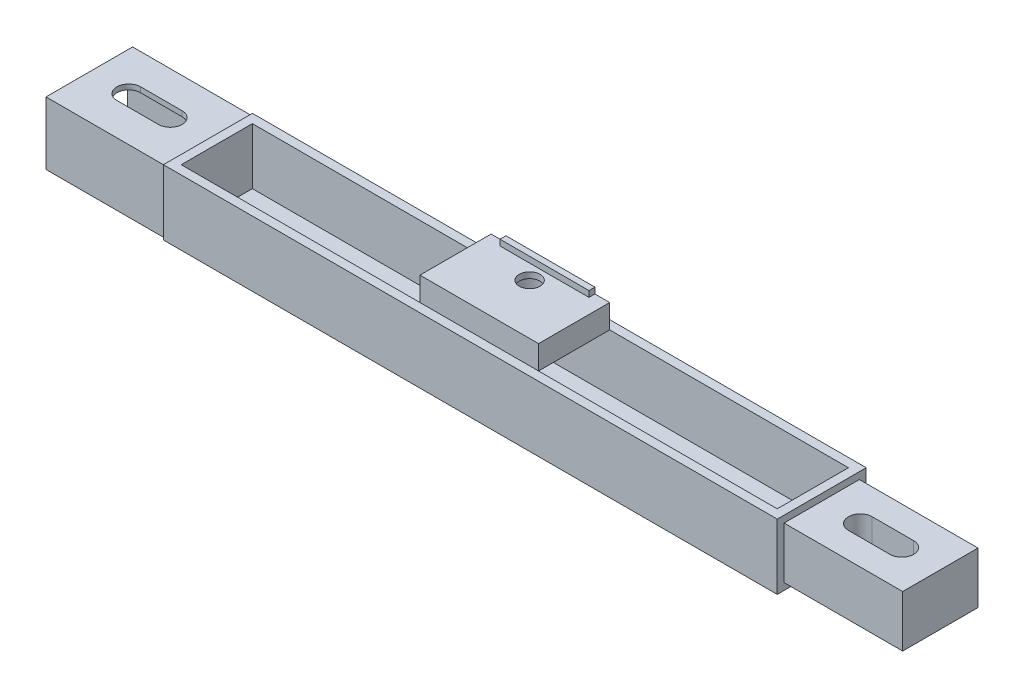
SolidWorks part; units mm, degrees
ref_plane "Front Plane" through (0, 0, 0) normal (0, 0, 1) x (1, 0, 0)
ref_plane "Top Plane" through (0, 0, 0) normal (0, 1, 0) x (1, 0, 0)
ref_plane "Right Plane" through (0, 0, 0) normal (1, 0, 0) x (0, 0, -1)
sketch "Sketch1" plane through (0, 0, 0) normal (0, 1, 0) x (1, 0, 0)
  line L1 (-103.5, -15) -> (103.5, -15)
  line L2 (-103.5, -15) -> (-103.5, 15)
  line L3 (-103.5, 15) -> (103.5, 15)
  line L4 (103.5, -15) -> (103.5, 15)
  line L5 (-103.5, -15) -> (103.5, 15) construction
  line L6 (-103.5, 15) -> (103.5, -15) construction
  point P0 (0, 0)
  dimension "D1" = 207
  dimension "D2" = 30
extrude "Boss-Extrude1" add sketch "Sketch1" along normal blind 22
shell "Shell1" thickness 3
sketch "Sketch2" plane through (0, 0, 0) normal (0, -1, 0) x (-1, 0, 0)
  line L0 (103.5, 15) -> (103.5, -15) construction
  line L1 (-103.5, 5) -> (103.5, 5)
  line L2 (-103.5, 5) -> (-103.5, -5)
  line L3 (-103.5, -5) -> (103.5, -5)
  line L4 (103.5, 5) -> (103.5, -5)
  line L5 (-103.5, 5) -> (103.5, -5) construction
  line L6 (-103.5, -5) -> (103.5, 5) construction
  point P0 (0, 0)
  dimension "D1" = 10
  dimension "D2" = 0
extrude "Cut-Extrude1" cut sketch "Sketch2" against normal blind 3
sketch "Sketch3" plane through (-103.5, 0, 0) normal (-1, 0, 0) x (0, 0, 1)
  line L0 (0, 22) -> (0, 0) construction
  line L1 (14.6, 0.4) -> (-14.6, 0.4)
  line L2 (14.6, 0.4) -> (14.6, 21.6)
  line L3 (14.6, 21.6) -> (-14.6, 21.6)
  line L4 (-14.6, 0.4) -> (-14.6, 21.6)
  line L5 (14.6, 0.4) -> (-14.6, 21.6) construction
  line L6 (14.6, 21.6) -> (-14.6, 0.4) construction
  line L7 (-15, 22) -> (15, 22) construction
  line L8 (-15, 11) -> (15, 11) construction
  line L9 (-15, 22) -> (-15, 0) construction
  line L10 (15, 22) -> (15, 0) construction
  point P0 (0, 11)
  dimension "D1" = 29.2
  dimension "D2" = 21.2
extrude "Boss-Extrude2" add sketch "Sketch3" along normal blind 40
sketch "Sketch4" plane through (-143.5, 0, 0) normal (-1, 0, 0) x (0, 0, 1)
  line L0 (0, 21.6) -> (0, 0.4) construction
  line L1 (-12.85, 2.15) -> (12.85, 2.15)
  line L2 (-12.85, 2.15) -> (-12.85, 19.85)
  line L3 (-12.85, 19.85) -> (12.85, 19.85)
  line L4 (12.85, 2.15) -> (12.85, 19.85)
  line L5 (-12.85, 2.15) -> (12.85, 19.85) construction
  line L6 (-12.85, 19.85) -> (12.85, 2.15) construction
  line L7 (14.6, 21.6) -> (-14.6, 21.6) construction
  line L8 (-14.6, 0.4) -> (14.6, 0.4) construction
  line L9 (-14.6, 11) -> (14.6, 11) construction
  line L10 (-14.6, 21.6) -> (-14.6, 0.4) construction
  line L11 (14.6, 0.4) -> (14.6, 21.6) construction
  point P0 (0, 11)
  dimension "D1" = 25.7
  dimension "D2" = 17.7
extrude "Cut-Extrude2" cut sketch "Sketch4" against normal blind 40
sketch "Sketch5" plane through (0, 21.6, 0) normal (0, 1, 0) x (1, 0, 0)
  line L0 (-130.5, 0.3067) -> (-116.5, 0.3067) construction
  line L1 (-130.5, 4.3067) -> (-116.5, 4.3067)
  line L2 (-130.5, -3.6933) -> (-116.5, -3.6933)
  line L3 (-143.5, -14.6) -> (-143.5, 14.6) construction
  arc A0 (-130.5, 4.3067) -> (-130.5, -3.6933) centre (-130.5, 0.3067) ccw
  arc A1 (-116.5, -3.6933) -> (-116.5, 4.3067) centre (-116.5, 0.3067) ccw
  point P2 (-123.5, 0.3067)
  dimension "D1" = 14
  dimension "D2" = 8
  dimension "D3" = 20
extrude "Cut-Extrude3" cut sketch "Sketch5" against normal through all
sketch "Sketch6" plane through (103.5, 0, 0) normal (1, 0, 0) x (0, 0, -1)
  line L0 (0, 22) -> (0, 0) construction
  line L1 (-12.7, 2.3) -> (12.7, 2.3)
  line L2 (-12.7, 2.3) -> (-12.7, 19.7)
  line L3 (-12.7, 19.7) -> (12.7, 19.7)
  line L4 (12.7, 2.3) -> (12.7, 19.7)
  line L5 (-12.7, 2.3) -> (12.7, 19.7) construction
  line L6 (-12.7, 19.7) -> (12.7, 2.3) construction
  line L7 (-15, 22) -> (15, 22) construction
  line L8 (-15, 11) -> (15, 11) construction
  line L9 (-15, 22) -> (-15, 0) construction
  line L10 (15, 22) -> (15, 0) construction
  point P0 (0, 11)
  dimension "D1" = 25.4
  dimension "D2" = 17.4
extrude "Boss-Extrude3" add sketch "Sketch6" along normal blind 40
sketch "Sketch7" plane through (0, 19.7, 0) normal (0, 1, 0) x (1, 0, 0)
  line L0 (116.5, 0) -> (130.5, 0) construction
  line L1 (116.5, 4) -> (130.5, 4)
  line L2 (116.5, -4) -> (130.5, -4)
  line L3 (143.5, 12.7) -> (143.5, -12.7) construction
  line L4 (103.5, 0) -> (143.5, 0) construction
  line L5 (103.5, -15) -> (103.5, 15) construction
  arc A0 (116.5, 4) -> (116.5, -4) centre (116.5, 0) ccw
  arc A1 (130.5, -4) -> (130.5, 4) centre (130.5, 0) ccw
  point P2 (123.5, 0)
  dimension "D1" = 14
  dimension "D2" = 8
  dimension "D3" = 20
extrude "Cut-Extrude4" cut sketch "Sketch7" against normal through all
sketch "Sketch8" plane through (0, 22, 0) normal (0, 1, 0) x (1, 0, 0)
  line L0 (-103.5, -15) -> (103.5, -15) construction
  line L1 (-20, 12) -> (20, 12)
  line L2 (-20, 12) -> (-20, -12)
  line L3 (-20, -12) -> (20, -12)
  line L4 (20, 12) -> (20, -12)
  line L5 (-20, 12) -> (20, -12) construction
  line L6 (-20, -12) -> (20, 12) construction
  line L7 (-103.5, -14.6) -> (-103.5, 14.6) construction
  point P0 (0, 0)
  dimension "D1" = 40
  dimension "D2" = 24
  dimension "D3" = 15
  dimension "D4" = 103.5
extrude "Boss-Extrude4" add sketch "Sketch8" along normal blind 8 separate body
sketch "Sketch9" plane through (0, 30, 0) normal (0, 1, 0) x (1, 0, 0)
  line L0 (-103.5, 15) -> (-103.5, -15) construction
  line L1 (-103.5, -15) -> (103.5, -15) construction
  circle A0 centre (0, 5) radius 3.5
  dimension "D1" = 7
  dimension "D2" = 103.5
  dimension "D3" = 20
extrude "Cut-Extrude6" cut sketch "Sketch9" against normal up to next (8 mm away)
sketch "Sketch10" plane through (0, 22, 0) normal (0, -1, 0) x (1, 0, 0)
  line L0 (-103.5, 5) -> (-103.5, 14.6) construction
  line L1 (-103.5, 15) -> (103.5, 15) construction
  circle A0 centre (0, -5) radius 6.5
  dimension "D1" = 13
  dimension "D2" = 103.5
  dimension "D3" = 20
extrude "Cut-Extrude10" cut sketch "Sketch10" against normal blind 6
sketch "Sketch11" plane through (0, 30, 0) normal (0, 1, 0) x (1, 0, 0)
  line L1 (-15, 10) -> (15, 10)
  line L2 (-15, 10) -> (-15, 12)
  line L3 (-15, 12) -> (15, 12)
  line L4 (15, 10) -> (15, 12)
  line L5 (-15, 10) -> (15, 12) construction
  line L6 (-15, 12) -> (15, 10) construction
  line L7 (0, 12) -> (0, -12) construction
  line L8 (20, 12) -> (-20, 12) construction
  line L9 (-100.5, -12) -> (100.5, -12) construction
  line L11 (-103.5, -15) -> (103.5, -15) construction
  point P0 (0, 11)
  dimension "D1" = 30
  dimension "D2" = 2
  dimension "D3" = 26
  dimension "D4" = 0
extrude "Boss-Extrude5" add sketch "Sketch11" along normal blind 2
